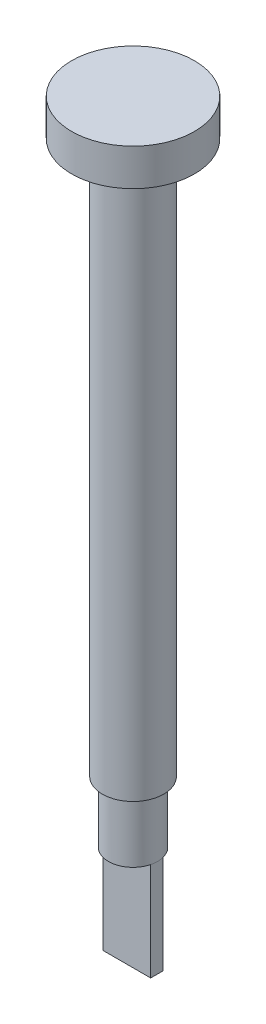
SolidWorks part; units mm, degrees
ref_plane "Front Plane" through (0, 0, 0) normal (0, 0, 1) x (1, 0, 0)
ref_plane "Top Plane" through (0, 0, 0) normal (0, 1, 0) x (1, 0, 0)
ref_plane "Right Plane" through (0, 0, 0) normal (1, 0, 0) x (0, 0, -1)
sketch "Sketch2" plane through (0, 0, 0) normal (0, 0, 1) x (1, 0, 0)
  line L0 (0, 0) -> (0, 50)
  line L1 (2, 0) -> (2, 5)
  line L2 (2, 5) -> (2.5, 5)
  line L3 (2.5, 5) -> (2.5, 50)
  line L5 (0, 0) -> (2, 0)
  line L10 (0, 50) -> (0, 53)
  line L11 (0, 53) -> (5, 53)
  line L12 (5, 53) -> (5, 50)
  line L13 (5, 50) -> (2.5, 50)
  dimension "D1" = 50
  dimension "D2" = 2.5
  dimension "D3" = 2
  dimension "D4" = 5
  dimension "D5" = 3
  dimension "D6" = 45
  dimension "D7" = 5
revolve "Revolve1" add sketch "Sketch2" angle 360 about L0
sketch "Sketch4" plane through (0, 0, 0) normal (0, -1, 0) x (1, 0, 0)
  line L0 (-1.9365, 0) -> (1.9365, 0) construction
  line L1 (-1.9365, 0.5) -> (1.9365, 0.5)
  line L2 (-1.9365, 0.5) -> (-1.9365, -0.5)
  line L3 (-1.9365, -0.5) -> (1.9365, -0.5)
  line L4 (1.9365, 0.5) -> (1.9365, -0.5)
  line L5 (0, 0.5) -> (0, -0.5) construction
  circle A0 centre (0, 0) radius 2 construction
  point P10 (-1.9216, -0.4457)
  dimension "D1" = 1
extrude "Boss-Extrude1" add sketch "Sketch4" along normal blind 8
